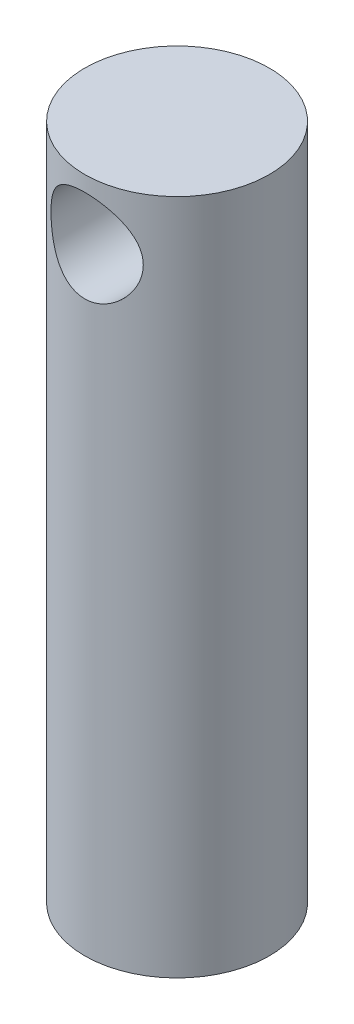
SolidWorks part; units mm, degrees
ref_plane "Front Plane" through (0, 0, 0) normal (0, 0, 1) x (1, 0, 0)
ref_plane "Top Plane" through (0, 0, 0) normal (0, 1, 0) x (1, 0, 0)
ref_plane "Right Plane" through (0, 0, 0) normal (1, 0, 0) x (0, 0, -1)
other "Center of Mass"
sketch "Sketch1" plane through (0, 0, 0) normal (0, 1, 0) x (1, 0, 0)
  circle A0 centre (0, 0) radius 15
extrude "Boss-Extrude1" add sketch "Sketch1" along normal blind 110
ref_plane "Plane2" through (0, 0, 20) normal (0, 0, 1) x (1, 0, 0)
sketch "Sketch2" plane through (0, 0, 20) normal (0, 0, 1) x (1, 0, 0)
  line L0 (0, 0) -> (0, 110) construction
  line L1 (15, 110) -> (-15, 110) construction
  circle A0 centre (0, 100) radius 7.5
  point P5 (0, 100)
  dimension "D2" = 15
  dimension "D1" = 10
extrude "Cut-Extrude1" cut sketch "Sketch2" against normal blind 40
ref_plane "Plane3" through (0, 100, 0) normal (0, 1, 0) x (1, 0, 0)
sketch "Sketch3" plane through (0, 100, 0) normal (0, 1, 0) x (1, 0, 0)
  line L0 (0, -15) -> (0, 15) construction
  line L1 (15, 0) -> (-15, 0) construction
  circle A0 centre (0, 0) radius 15 construction
  point P0 (0, 0)
  point P7 (0, 0)
  point P11 (0, 0)
